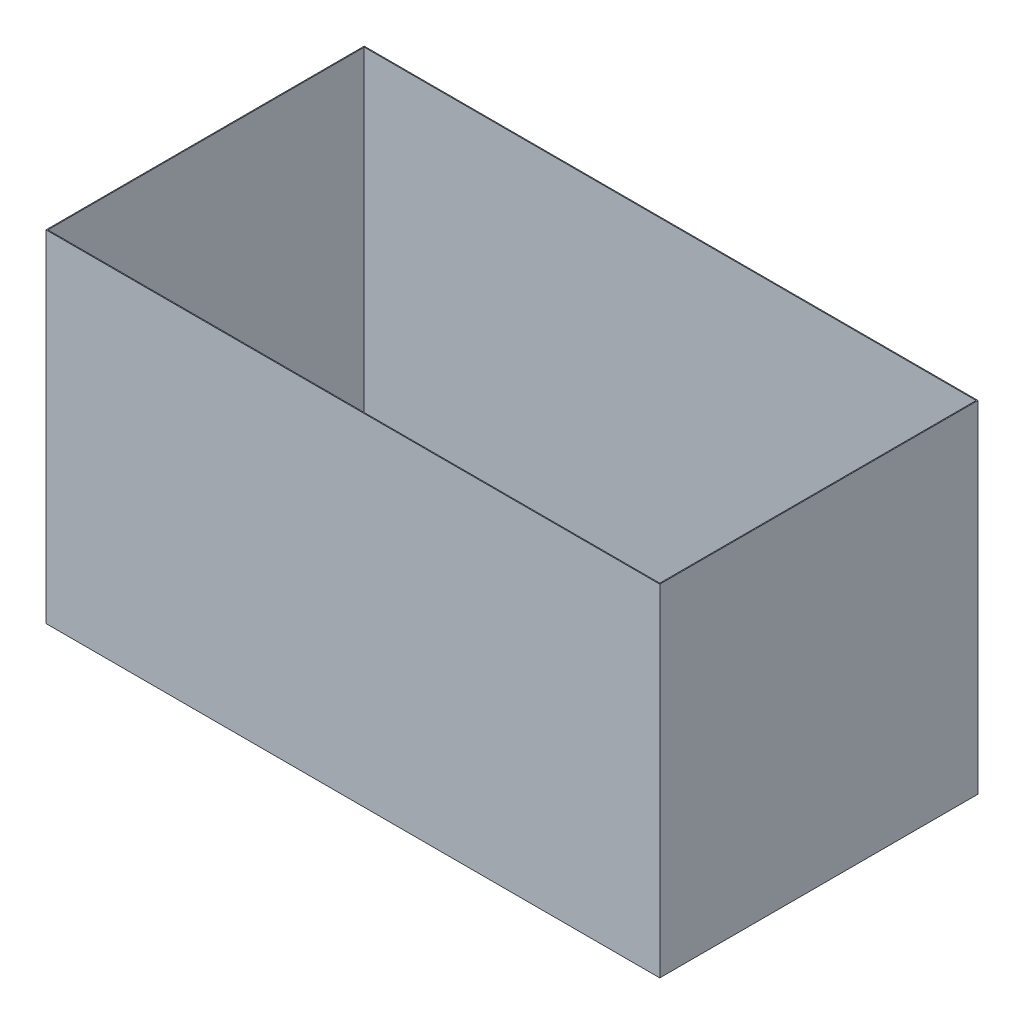
SolidWorks part; units mm, degrees
ref_plane "Спереди" through (0, 0, 0) normal (0, 0, 1) x (1, 0, 0)
ref_plane "Сверху" through (0, 0, 0) normal (0, 1, 0) x (1, 0, 0)
ref_plane "Справа" through (0, 0, 0) normal (1, 0, 0) x (0, 0, -1)
sketch "MASTER_FOOTPRINT" plane through (0, 0, 0) normal (0, 1, 0) x (1, 0, 0)
  line L1 (0, 0) -> (1350, 0)
  line L2 (0, 0) -> (0, 700)
  line L3 (0, 700) -> (1350, 700)
  line L4 (1350, 0) -> (1350, 700)
  dimension "D1" = 1350
  dimension "D2" = 700
extrude "BATH_BASE_PLATE" add sketch "MASTER_FOOTPRINT" along normal blind 750
shell "BATH_SHELL_2MM" thickness 2
equation "\"AI_Q_Peak\"= 0.006"
equation "\"AI_B_Bath\"= 700"
equation "\"AI_L_Settle\"= 900"
equation "\"AI_L_Inlet\"= 250"
equation "\"AI_L_Outlet\"= 200"
equation "\"AI_L_Bath\"= 1350"
equation "\"AI_H_Water\"= 550"
equation "\"AI_H_Freeboard\"= 200"
equation "\"AI_H_Bath\"= 750"
equation "\"AI_Shell_Thickness\"= 2"
equation "\"AI_Inlet_DN\"= 100"
equation "\"AI_Weir_Width\"= 600"
equation "\"AI_Inlet_Baffle_Offset\"= 125"
equation "\"AI_Distributor_Open_Area\"= 0.28"
equation "\"AI_Distributor_Hole_Dia\"= 22"
equation "\"AI_Distributor_Blind_Zone\"= 110"
equation "\"AI_Outlet_Baffle_Depth\"= 250"
equation "\"AI_Screw_Diameter\"= 100"
equation "\"AI_Screw_Pitch\"= 100"
equation "\"AI_Screw_Angle\"= 30"
equation "\"AI_Screw_Rpm\"= 15"
equation "\"AI_Screw_Clearance\"= 5"
equation "\"AI_Liner_Thickness\"= 5"
equation "\"AI_Discharge_Height\"= 650"
equation "\"AI_Frame_Height\"= 500"
equation "\"D1@MASTER_FOOTPRINT\" = \"AI_L_Bath\""
equation "\"D2@MASTER_FOOTPRINT\" = \"AI_B_Bath\""
equation "\"D1@BATH_BASE_PLATE\" = \"AI_H_Bath\""
